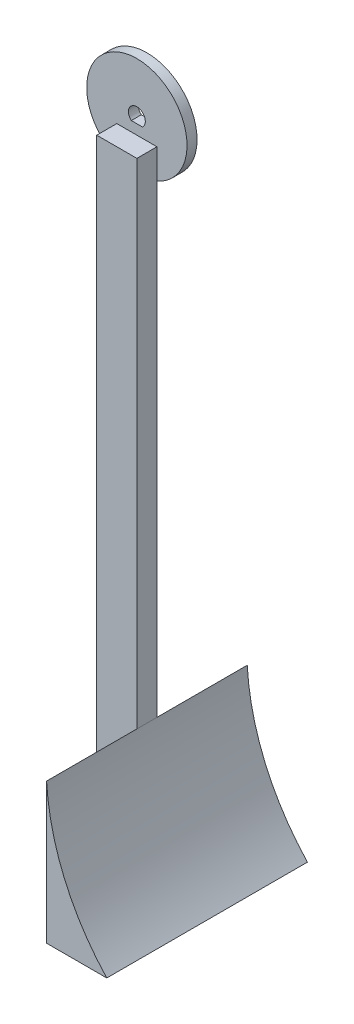
SolidWorks part; units mm, degrees
ref_plane "Front Plane" through (0, 0, 0) normal (0, 0, 1) x (1, 0, 0)
ref_plane "Top Plane" through (0, 0, 0) normal (0, 1, 0) x (1, 0, 0)
ref_plane "Right Plane" through (0, 0, 0) normal (1, 0, 0) x (0, 0, -1)
sketch "Sketch2" plane through (0, 0, 0) normal (0, 0, 1) x (1, 0, 0)
  line L0 (0, 2.1) -> (0, -1.575)
  line L1 (0, -13.75) -> (0, 13.75) construction
  line L2 (0, -1.575) -> (1.389, -1.575)
  line L3 (0, -1.575) -> (-1.389, -1.575)
  circle A0 centre (0, 0) radius 12.5
  arc A1 (1.389, -1.575) -> (-1.389, -1.575) centre (0, 0) ccw
  dimension "D1" = 4.2
extrude "Boss-Extrude1" add sketch "Sketch2" along normal blind 2.5 contours A0 A1 L2 L3
ref_plane "Plane1" through (0, 0, 2.5) normal (0, 0, 1) x (1, 0, 0)
sketch "Sketch4" plane through (0, 0, 2.5) normal (0, 0, 1) x (1, 0, 0)
  line L0 (-5, -162.1706) -> (5, -162.1706)
  line L1 (0, -13.75) -> (0, 13.75) construction
  line L2 (0, -5) -> (0, -4.0383)
  line L3 (0, -4.0383) -> (5, -4.0383)
  line L4 (0, -4.0383) -> (-5, -4.0383)
  line L5 (-5, -4.0383) -> (-5, -162.1706)
  line L6 (5, -162.1706) -> (5, -4.0383)
  point P1 (0, 0)
  dimension "D1" = 158.1323
extrude "Boss-Extrude2" add sketch "Sketch4" along normal blind 5 contours L0 L6 L3 L4 L5
ref_plane "Plane2" through (5, 0, 0) normal (1, 0, 0) x (0, 0, -1)
sketch "Sketch5" plane through (5, 0, 0) normal (1, 0, 0) x (0, 0, -1)
  line L0 (-7.5, -162.1706) -> (-2.5, -162.1706) construction
  line L4 (20, -127.1706) -> (20, -162.1706)
  line L5 (-30, -127.1706) -> (-30, -162.1706)
  line L7 (-30, -162.1706) -> (20, -162.1706)
  line L10 (-30, -127.1706) -> (20, -127.1706)
  line L11 (-7.5, -162.1706) -> (-2.5, -162.1706)
  point P2 (-5, -162.1706)
  point P3 (-5, -162.1706)
  dimension "D1" = 35
  dimension "D2" = 50
extrude "Boss-Extrude3" add sketch "Sketch5" along normal blind 15
sketch "Sketch6" plane through (0, 0, -20) normal (0, 0, -1) x (-1, 0, 0)
  line L2 (-20, -127.1706) -> (-5, -127.1706) construction
  line L3 (-20, -127.1706) -> (-20, -162.1706) construction
  line L4 (-20, -127.1706) -> (-5, -127.1706)
  line L5 (-20, -127.1706) -> (-20, -162.1706)
  arc A0 (-5, -127.1706) -> (-20, -162.1706) centre (-60.9882, -123.8899) cw
  point P0 (-18.8196, -146.2966)
  point P3 (0, 0)
  point P4 (0, 0)
  point P5 (0, 0)
  point P6 (-5, -110.0856)
extrude "Cut-Extrude1" cut sketch "Sketch6" against normal through all both and the other way through all
